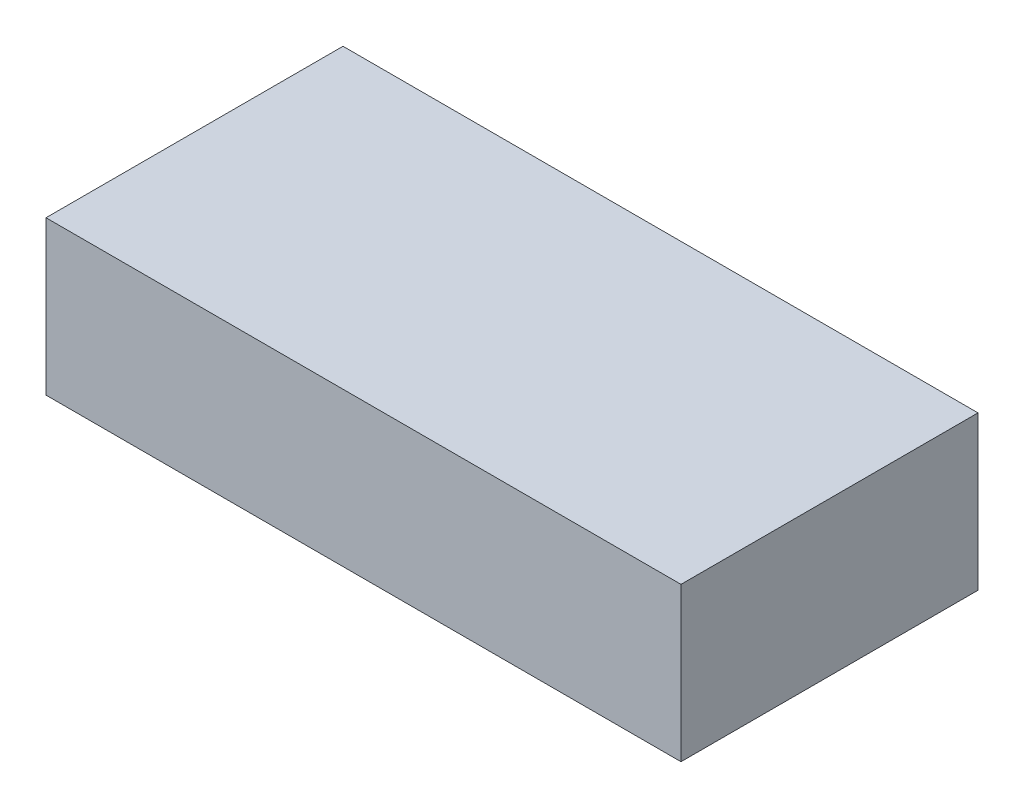
SolidWorks part; units mm, degrees
ref_plane "前视基准面" through (0, 0, 0) normal (0, 0, 1) x (1, 0, 0)
ref_plane "上视基准面" through (0, 0, 0) normal (0, 1, 0) x (1, 0, 0)
ref_plane "右视基准面" through (0, 0, 0) normal (1, 0, 0) x (0, 0, -1)
sketch "草图1" plane through (0, 0, 0) normal (0, 1, 0) x (1, 0, 0)
  line L1 (0, 0) -> (62, 0)
  line L2 (0, 0) -> (0, 29)
  line L3 (0, 29) -> (62, 29)
  line L4 (62, 0) -> (62, 29)
  dimension "D1" = 62
  dimension "D2" = 29
extrude "凸台-拉伸1" add sketch "草图1" along normal blind 15
